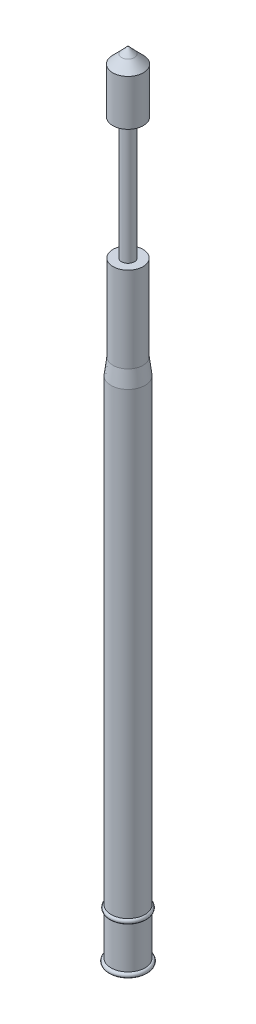
SolidWorks part; units mm, degrees
ref_plane "前视基准面" through (0, 0, 0) normal (0, 0, 1) x (1, 0, 0)
ref_plane "上视基准面" through (0, 0, 0) normal (0, 1, 0) x (1, 0, 0)
ref_plane "右视基准面" through (0, 0, 0) normal (1, 0, 0) x (0, 0, -1)
other "Configuration Table"
sketch "草图1" plane through (0, 0, 0) normal (0, 1, 0) x (1, 0, 0)
  circle A0 centre (0, 0) radius 0.835
  dimension "D1" = 1.67
extrude "凸台-拉伸1" add sketch "草图1" along normal blind 25
sketch "草图2" plane through (0, 25, 0) normal (0, 1, 0) x (1, 0, 0)
  circle A0 centre (0, 0) radius 0.735
  dimension "D1" = 1.47
extrude "凸台-拉伸2" add sketch "草图2" along normal blind 5
sketch "草图3" plane through (0, 30, 0) normal (0, 1, 0) x (1, 0, 0)
  circle A0 centre (0, 0) radius 0.32
  dimension "D1" = 0.64
extrude "凸台-拉伸3" add sketch "草图3" along normal blind 9
sketch "草图5" plane through (0, 0, 0) normal (0, 0, 1) x (1, 0, 0)
  line L0 (0.835, 25) -> (0.735, 25.8)
  line L1 (0.735, 25) -> (0.735, 30) construction
  line L2 (0.735, 25.8) -> (0.735, 25)
  line L3 (0.735, 25) -> (0.835, 25)
  line L4 (0, 0) -> (0, 0.7809) construction
  line L7 (0, 0.115) -> (0.95, 0.115) construction
  line L8 (0.835, 0) -> (0.835, 25) construction
  line L9 (0.835, 0.23) -> (0.835, 0)
  line L10 (-0.835, 0) -> (0.835, 0) construction
  line L11 (0, 2.385) -> (0.915, 2.385) construction
  line L12 (0.835, 2.5) -> (0.835, 2.27)
  arc A0 (0.835, 0.23) -> (0.835, 0) centre (0.835, 0.115) cw
  arc A1 (0.835, 2.5) -> (0.835, 2.27) centre (0.7923, 2.385) cw
  dimension "D1" = 0.8
  dimension "D2" = 0.95
  dimension "D3" = 0.915
  dimension "D4" = 2.5
revolve "旋转1" add sketch "草图5" angle 360 about L4
sketch "草图6" plane through (0, 0, 0) normal (0, 0, 1) x (1, 0, 0)
  line L0 (0, 0) -> (0, -1.2565) construction
  line L2 (0, 39) -> (-0.75, 38.25)
  line L3 (0.32, 39) -> (-0.32, 39) construction
  line L4 (-0.75, 38.25) -> (-0.75, 36)
  line L5 (-0.75, 36) -> (0, 36)
  line L6 (0, 36) -> (0, 39)
  point P7 (-1, 38)
  dimension "D1" = 0.75
  dimension "D2" = 3
  dimension "D3" = 135
revolve "旋转2" add sketch "草图6" angle 360 about L0
sketch "草图7" plane through (0, 0, 0) normal (0, 0, 1) x (1, 0, 0)
  line L0 (0, 0) -> (0, -1.5384) construction
  line L7 (0.32, 39) -> (0.02, 39)
  line L8 (0.32, 39) -> (-0.32, 39) construction
  line L9 (0.02, 39) -> (0.32, 38.68)
  line L10 (0.32, 38.68) -> (-0.32, 38.68) construction
  line L11 (0.32, 38.68) -> (0.32, 39) construction
  line L12 (0.32, 38.68) -> (0.32, 39)
  dimension "D1" = 0.3
revolve "切除-旋转5" cut sketch "草图7" angle 360 about L0
